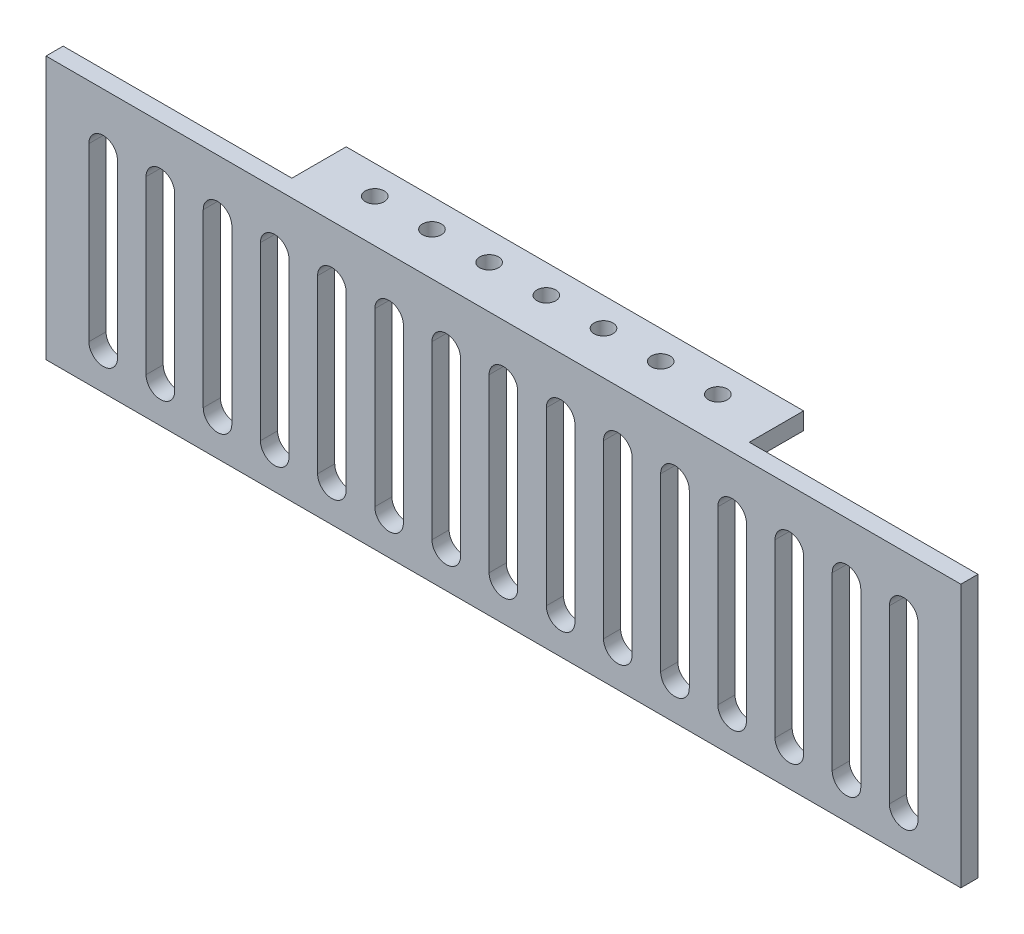
SolidWorks part; units mm, degrees
ref_plane "前视基准面" through (0, 0, 0) normal (0, 0, 1) x (1, 0, 0)
ref_plane "上视基准面" through (0, 0, 0) normal (0, 1, 0) x (1, 0, 0)
ref_plane "右视基准面" through (0, 0, 0) normal (1, 0, 0) x (0, 0, -1)
sketch "草图1" plane through (0, 0, 0) normal (0, 1, 0) x (1, 0, 0)
  line L1 (-40, 7.5) -> (40, 7.5)
  line L2 (-40, 7.5) -> (-40, -7.5)
  line L3 (-40, -7.5) -> (40, -7.5)
  line L4 (40, 7.5) -> (40, -7.5)
  line L5 (-40, 7.5) -> (40, -7.5) construction
  line L6 (-40, -7.5) -> (40, 7.5) construction
  point P0 (0, 0)
  dimension "D1" = 80
  dimension "D2" = 15
extrude "凸台-拉伸1" add sketch "草图1" along normal blind 3
sketch "草图2" plane through (0, 3, 0) normal (0, 1, 0) x (1, 0, 0)
  line L0 (40, 7.5) -> (-40, 7.5) construction
  line L2 (-40, 7.5) -> (-40, -7.5) construction
  circle A0 centre (-30, 2.5) radius 1.65
  circle A1 centre (-20, 2.5) radius 1.65
  circle A2 centre (-10, 2.5) radius 1.65
  circle A3 centre (0, 2.5) radius 1.65
  circle A4 centre (10, 2.5) radius 1.65
  circle A5 centre (20, 2.5) radius 1.65
  circle A6 centre (30, 2.5) radius 1.65
  dimension "D1" = 3.3
  dimension "D2" = 5
  dimension "D3" = 10
  dimension "D5" = 10
  dimension "D4" = 7
extrude "切除-拉伸1" cut sketch "草图2" against normal blind 3
sketch "草图3" plane through (0, 0, 0) normal (0, -1, 0) x (1, 0, 0)
  line L0 (-40, -7.5) -> (-40, 7.5) construction
  line L1 (-40, 5) -> (40, 5)
  line L2 (-40, 5) -> (-40, 2)
  line L3 (-40, 2) -> (40, 2)
  line L4 (40, 5) -> (40, 2)
  line L5 (40, 7.5) -> (40, -7.5) construction
  circle A0 centre (30, -2.5) radius 1.65 construction
  dimension "D1" = 3
  dimension "D2" = 4.5
extrude "凸台-拉伸2" add sketch "草图3" along normal blind 43 contours L2 L1 L4 L3
sketch "草图4" plane through (40, 0, 0) normal (1, 0, 0) x (0, 0, -1)
  line L0 (-7.5, 3) -> (7.5, 3) construction
  line L5 (-5, 3) -> (-2, 3)
  line L6 (-5, 3) -> (-5, -43)
  line L7 (-5, -43) -> (-2, -43)
  line L8 (-2, 3) -> (-2, -43)
extrude "凸台-拉伸3" add sketch "草图4" along normal blind 40
sketch "草图5" plane through (-40, 0, 0) normal (-1, 0, 0) x (0, 0, 1)
  line L5 (2, -43) -> (5, -43)
  line L6 (2, -43) -> (2, 3)
  line L7 (2, 3) -> (5, 3)
  line L8 (5, -43) -> (5, 3)
  line L10 (-7.5, 3) -> (7.5, 3) construction
extrude "凸台-拉伸4" add sketch "草图5" along normal blind 40
sketch "草图8" plane through (-40, 0, 0) normal (-1, 0, 0) x (0, 0, 1)
  line L1 (5, 0) -> (7.5, 0)
  line L2 (5, 0) -> (5, 3)
  line L3 (5, 3) -> (7.5, 3)
  line L4 (7.5, 0) -> (7.5, 3)
extrude "切除-拉伸3" cut sketch "草图8" against normal blind 80
sketch "草图9" plane through (0, 0, 2) normal (0, 0, -1) x (-1, 0, 0)
  line L0 (-70, -6.5208) -> (-70, -36.5208) construction
  line L1 (-67.5, -6.5208) -> (-67.5, -36.5208)
  line L2 (-72.5, -6.5208) -> (-72.5, -36.5208)
  line L3 (-80, -43) -> (-80, 3) construction
  line L4 (-60, -6.5208) -> (-60, -36.5208) construction
  line L5 (-57.5, -6.5208) -> (-57.5, -36.5208)
  line L6 (-62.5, -6.5208) -> (-62.5, -36.5208)
  line L7 (-50, -6.5208) -> (-50, -36.5208) construction
  line L8 (-47.5, -6.5208) -> (-47.5, -36.5208)
  line L9 (-52.5, -6.5208) -> (-52.5, -36.5208)
  line L10 (-40, -6.5208) -> (-40, -36.5208) construction
  line L11 (-37.5, -6.5208) -> (-37.5, -36.5208)
  line L12 (-42.5, -6.5208) -> (-42.5, -36.5208)
  line L13 (-30, -6.5208) -> (-30, -36.5208) construction
  line L14 (-27.5, -6.5208) -> (-27.5, -36.5208)
  line L15 (-32.5, -6.5208) -> (-32.5, -36.5208)
  line L16 (-20, -6.5208) -> (-20, -36.5208) construction
  line L17 (-17.5, -6.5208) -> (-17.5, -36.5208)
  line L18 (-22.5, -6.5208) -> (-22.5, -36.5208)
  line L19 (-10, -6.5208) -> (-10, -36.5208) construction
  line L20 (-7.5, -6.5208) -> (-7.5, -36.5208)
  line L21 (-12.5, -6.5208) -> (-12.5, -36.5208)
  line L22 (0, -6.5208) -> (0, -36.5208) construction
  line L23 (2.5, -6.5208) -> (2.5, -36.5208)
  line L24 (-2.5, -6.5208) -> (-2.5, -36.5208)
  line L25 (10, -6.5208) -> (10, -36.5208) construction
  line L26 (12.5, -6.5208) -> (12.5, -36.5208)
  line L27 (7.5, -6.5208) -> (7.5, -36.5208)
  line L28 (20, -6.5208) -> (20, -36.5208) construction
  line L29 (22.5, -6.5208) -> (22.5, -36.5208)
  line L30 (17.5, -6.5208) -> (17.5, -36.5208)
  line L31 (30, -6.5208) -> (30, -36.5208) construction
  line L32 (32.5, -6.5208) -> (32.5, -36.5208)
  line L33 (27.5, -6.5208) -> (27.5, -36.5208)
  line L34 (40, -6.5208) -> (40, -36.5208) construction
  line L35 (42.5, -6.5208) -> (42.5, -36.5208)
  line L36 (37.5, -6.5208) -> (37.5, -36.5208)
  line L37 (50, -6.5208) -> (50, -36.5208) construction
  line L38 (52.5, -6.5208) -> (52.5, -36.5208)
  line L39 (47.5, -6.5208) -> (47.5, -36.5208)
  line L40 (60, -6.5208) -> (60, -36.5208) construction
  line L41 (62.5, -6.5208) -> (62.5, -36.5208)
  line L42 (57.5, -6.5208) -> (57.5, -36.5208)
  line L43 (70, -6.5208) -> (70, -36.5208) construction
  line L44 (72.5, -6.5208) -> (72.5, -36.5208)
  line L45 (67.5, -6.5208) -> (67.5, -36.5208)
  arc A0 (-67.5, -6.5208) -> (-72.5, -6.5208) centre (-70, -6.5208) ccw
  arc A1 (-72.5, -36.5208) -> (-67.5, -36.5208) centre (-70, -36.5208) ccw
  arc A2 (-57.5, -6.5208) -> (-62.5, -6.5208) centre (-60, -6.5208) ccw
  arc A3 (-62.5, -36.5208) -> (-57.5, -36.5208) centre (-60, -36.5208) ccw
  arc A4 (-47.5, -6.5208) -> (-52.5, -6.5208) centre (-50, -6.5208) ccw
  arc A5 (-52.5, -36.5208) -> (-47.5, -36.5208) centre (-50, -36.5208) ccw
  arc A6 (-37.5, -6.5208) -> (-42.5, -6.5208) centre (-40, -6.5208) ccw
  arc A7 (-42.5, -36.5208) -> (-37.5, -36.5208) centre (-40, -36.5208) ccw
  arc A8 (-27.5, -6.5208) -> (-32.5, -6.5208) centre (-30, -6.5208) ccw
  arc A9 (-32.5, -36.5208) -> (-27.5, -36.5208) centre (-30, -36.5208) ccw
  arc A10 (-17.5, -6.5208) -> (-22.5, -6.5208) centre (-20, -6.5208) ccw
  arc A11 (-22.5, -36.5208) -> (-17.5, -36.5208) centre (-20, -36.5208) ccw
  arc A12 (-7.5, -6.5208) -> (-12.5, -6.5208) centre (-10, -6.5208) ccw
  arc A13 (-12.5, -36.5208) -> (-7.5, -36.5208) centre (-10, -36.5208) ccw
  arc A14 (2.5, -6.5208) -> (-2.5, -6.5208) centre (0, -6.5208) ccw
  arc A15 (-2.5, -36.5208) -> (2.5, -36.5208) centre (0, -36.5208) ccw
  arc A16 (12.5, -6.5208) -> (7.5, -6.5208) centre (10, -6.5208) ccw
  arc A17 (7.5, -36.5208) -> (12.5, -36.5208) centre (10, -36.5208) ccw
  arc A18 (22.5, -6.5208) -> (17.5, -6.5208) centre (20, -6.5208) ccw
  arc A19 (17.5, -36.5208) -> (22.5, -36.5208) centre (20, -36.5208) ccw
  arc A20 (32.5, -6.5208) -> (27.5, -6.5208) centre (30, -6.5208) ccw
  arc A21 (27.5, -36.5208) -> (32.5, -36.5208) centre (30, -36.5208) ccw
  arc A22 (42.5, -6.5208) -> (37.5, -6.5208) centre (40, -6.5208) ccw
  arc A23 (37.5, -36.5208) -> (42.5, -36.5208) centre (40, -36.5208) ccw
  arc A24 (52.5, -6.5208) -> (47.5, -6.5208) centre (50, -6.5208) ccw
  arc A25 (47.5, -36.5208) -> (52.5, -36.5208) centre (50, -36.5208) ccw
  arc A26 (62.5, -6.5208) -> (57.5, -6.5208) centre (60, -6.5208) ccw
  arc A27 (57.5, -36.5208) -> (62.5, -36.5208) centre (60, -36.5208) ccw
  arc A28 (72.5, -6.5208) -> (67.5, -6.5208) centre (70, -6.5208) ccw
  arc A29 (67.5, -36.5208) -> (72.5, -36.5208) centre (70, -36.5208) ccw
  point P2 (-70, -21.5208)
  point P12 (-60, -21.5208)
  point P19 (-50, -21.5208)
  point P26 (-40, -21.5208)
  point P33 (-30, -21.5208)
  point P40 (-20, -21.5208)
  point P47 (-10, -21.5208)
  point P54 (0, -21.5208)
  point P61 (10, -21.5208)
  point P68 (20, -21.5208)
  point P75 (30, -21.5208)
  point P82 (40, -21.5208)
  point P89 (50, -21.5208)
  point P96 (60, -21.5208)
  point P103 (70, -21.5208)
  dimension "D1" = 5
  dimension "D2" = 30
  dimension "D3" = 10
  dimension "D5" = 10
  dimension "D4" = 15
extrude "切除-拉伸4" cut sketch "草图9" against normal blind 80
